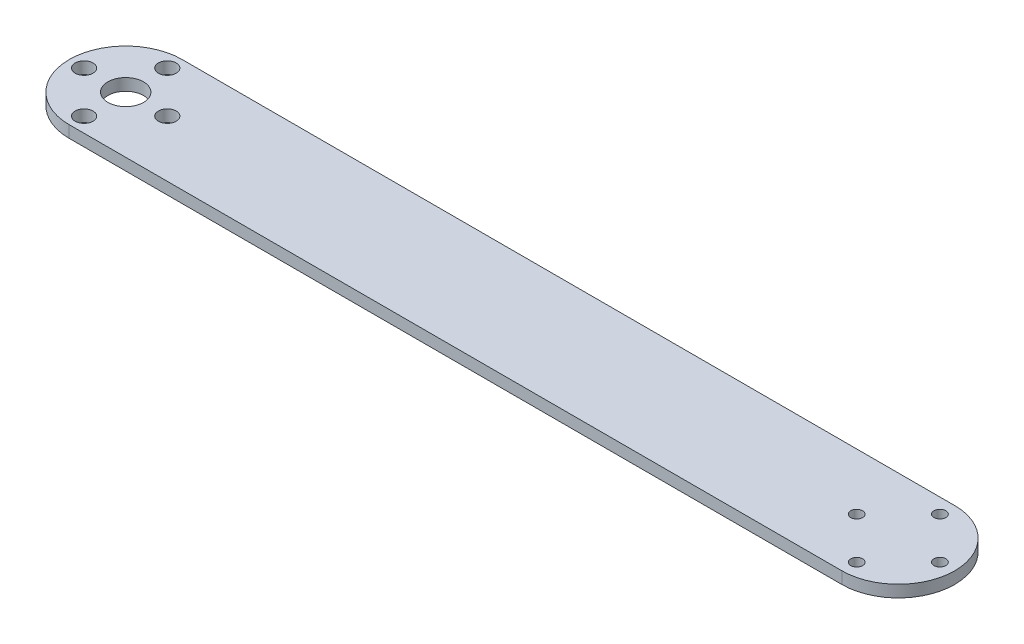
SolidWorks part; units mm, degrees
material "1060 Сплав"
ref_plane "Спереди" through (0, 0, 0) normal (0, 0, 1) x (1, 0, 0)
ref_plane "Сверху" through (0, 0, 0) normal (0, 1, 0) x (1, 0, 0)
ref_plane "Справа" through (0, 0, 0) normal (1, 0, 0) x (0, 0, -1)
sketch "Эскиз1" plane through (0, 0, 0) normal (0, 1, 0) x (1, 0, 0)
  line L0 (0, 9.5) -> (130, 9.5)
  line L1 (0, -9.5) -> (130, -9.5)
  arc A0 (0, 9.5) -> (0, -9.5) centre (0, 0) ccw
  circle A1 centre (0, 0) radius 7 construction
  circle A2 centre (0, 7) radius 1.5
  circle A3 centre (7, 0) radius 1.5
  circle A4 centre (0, -7) radius 1.5
  circle A5 centre (-7, 0) radius 1.5
  arc A6 (130, -9.5) -> (130, 9.5) centre (130, 0) ccw
  circle A7 centre (130, 0) radius 7 construction
  circle A8 centre (130, 7) radius 1
  circle A9 centre (137, 0) radius 1
  circle A10 centre (123, 0) radius 1
  circle A11 centre (130, -7) radius 1
  circle A12 centre (130, 0) radius 8 construction
  circle A13 centre (0, 0) radius 3
  point P31 (130, 0)
  dimension "D1" = 14
  dimension "D2" = 3
  dimension "D3" = 19
  dimension "D4" = 14
  dimension "D5" = 16
  dimension "D7" = 6
  dimension "D6" = 130
extrude "Бобышка-Вытянуть1" add sketch "Эскиз1" along normal blind 2
